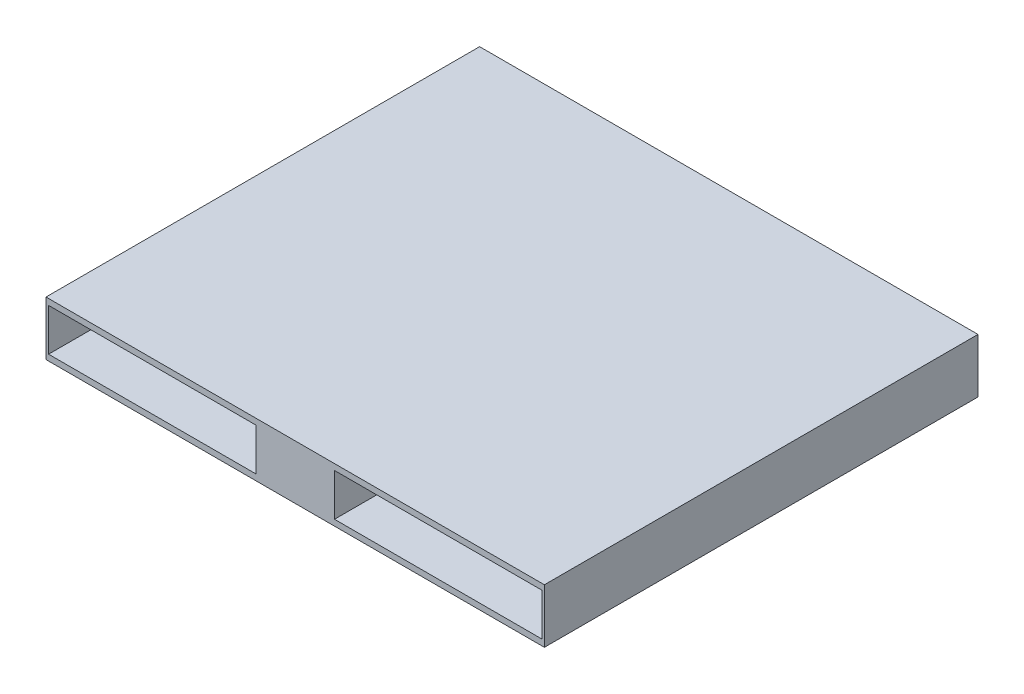
SolidWorks part; units mm, degrees
ref_plane "Alzado" through (0, 0, 0) normal (0, 0, 1) x (1, 0, 0)
ref_plane "Planta" through (0, 0, 0) normal (0, 1, 0) x (1, 0, 0)
ref_plane "Vista lateral" through (0, 0, 0) normal (1, 0, 0) x (0, 0, -1)
sketch "Croquis1" plane through (0, 0, 0) normal (0, 1, 0) x (1, 0, 0)
  line L1 (0, 0) -> (1200, 0)
  line L2 (0, 0) -> (0, 800)
  line L3 (0, 800) -> (1200, 800)
  line L4 (1200, 0) -> (1200, 800)
  dimension "D1" = 1200
  dimension "D2" = 800
extrude "Saliente-Extruir1" add sketch "Croquis1" along normal blind 100
sketch "Croquis2" plane through (0, 0, 0) normal (0, 0, 1) x (1, 0, 0)
  line L0 (0, 0) -> (1200, 0) construction
  line L1 (0, 100) -> (145, 100) construction
  line L2 (0, 100) -> (0, 0) construction
  line L3 (0, 0) -> (145, 0) construction
  line L4 (145, 100) -> (145, 0) construction
  line L5 (672.5, 100) -> (672.5, 0) construction
  line L6 (527.5, 0) -> (672.5, 0) construction
  line L7 (527.5, 100) -> (527.5, 0) construction
  line L8 (527.5, 100) -> (672.5, 100) construction
  line L9 (1200, 100) -> (1200, 0) construction
  line L10 (1055, 0) -> (1200, 0) construction
  line L11 (1055, 100) -> (1055, 0) construction
  line L12 (1055, 100) -> (1200, 100) construction
  line L13 (145, 100) -> (672.5, 100) construction
  line L14 (145, 50) -> (527.5, 50) construction
  line L23 (672.5, 50) -> (1055, 50) construction
  line L24 (145, 11) -> (527.5, 11)
  line L25 (145, 11) -> (145, 89)
  line L26 (527.5, 11) -> (527.5, 89)
  line L27 (145, 89) -> (527.5, 89)
  line L28 (145, 11) -> (527.5, 89) construction
  line L29 (527.5, 11) -> (145, 89) construction
  line L30 (600, 100) -> (600, 0) construction
  line L31 (672.5, 11) -> (672.5, 89)
  line L32 (1055, 89) -> (672.5, 89)
  line L33 (1055, 11) -> (1055, 89)
  line L34 (1055, 11) -> (672.5, 11)
  point P22 (336.25, 50)
  dimension "D1" = 145
  dimension "D3" = 527.5
  dimension "D4" = 78
  dimension "D2" = 3
extrude "Cortar-Extruir2" cut sketch "Croquis2" against normal through all
sketch "Croquis3" plane through (0, 0, 0) normal (0, 0, 1) x (1, 0, 0)
  line L0 (0, 0) -> (1200, 0) construction
  line L1 (0, 100) -> (140.2375, 100)
  line L2 (0, 100) -> (0, 0)
  line L3 (0, 0) -> (140.2375, 0)
  line L4 (140.2375, 100) -> (140.2375, 0)
  line L5 (1055, 11) -> (1055, 89) construction
  line L6 (1200, 100) -> (1059.7625, 100)
  line L7 (1200, 100) -> (1200, 0)
  line L8 (1200, 0) -> (1059.7625, 0)
  line L9 (1059.7625, 100) -> (1059.7625, 0)
  line L10 (145, 89) -> (145, 11) construction
  dimension "D1" = 4.7625
  dimension "D2" = 4.7625
extrude "Cortar-Extruir3" cut sketch "Croquis3" against normal through all
